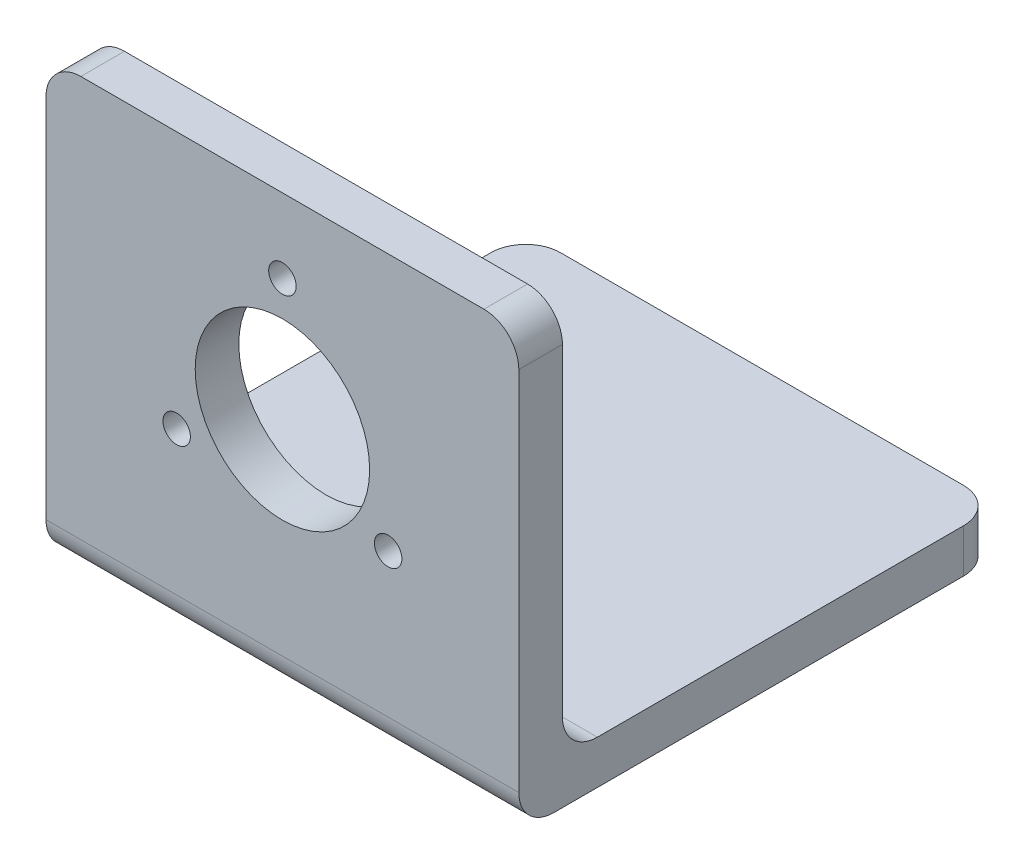
SolidWorks part; units mm, degrees
ref_plane "Front Plane" through (0, 0, 0) normal (0, 0, 1) x (1, 0, 0)
ref_plane "Top Plane" through (0, 0, 0) normal (0, 1, 0) x (1, 0, 0)
ref_plane "Right Plane" through (0, 0, 0) normal (1, 0, 0) x (0, 0, -1)
sketch "Sketch1" plane through (0, 0, 0) normal (0, 0, 1) x (1, 0, 0)
  line L0 (0, 0) -> (0, 14) construction
  line L1 (-27.106, -22.5) -> (27.106, -22.5)
  line L2 (-27.106, -22.5) -> (-27.106, 22.5)
  line L3 (-27.106, 22.5) -> (27.106, 22.5)
  line L4 (27.106, -22.5) -> (27.106, 22.5)
  line L5 (-27.106, -22.5) -> (27.106, 22.5) construction
  line L6 (-27.106, 22.5) -> (27.106, -22.5) construction
  circle A0 centre (0, 0) radius 10
  circle A1 centre (0, 14) radius 1.575
  circle A2 centre (12.1244, -7) radius 1.575
  circle A3 centre (-12.1244, -7) radius 1.575
  point P0 (0, 0)
  point P17 (0, 0)
  dimension "D1" = 20
  dimension "D3" = 3.15
  dimension "D2" = 14
  dimension "D5" = 22.5
  dimension "D4" = 3
extrude "Boss-Extrude1" add sketch "Sketch1" along normal blind 5
sketch "Sketch2" plane through (0, 0, 0) normal (0, 0, -1) x (-1, 0, 0)
  line L6 (-27.106, -22.5) -> (27.106, -22.5)
  line L7 (-27.106, -22.5) -> (-27.106, -27.5)
  line L8 (-27.106, -27.5) -> (27.106, -27.5)
  line L9 (27.106, -22.5) -> (27.106, -27.5)
  dimension "D1" = 5
extrude "Boss-Extrude2" add sketch "Sketch2" along normal blind 50 and the other way blind 5
fillet "Fillet3" radius 4 6 edges at (-27.106, -25, -50) (-27.106, 22.5, 2.5) (27.106, 22.5, 2.5) (0, -22.5, 0) (0, -27.5, 5) (27.106, -25, -50)
